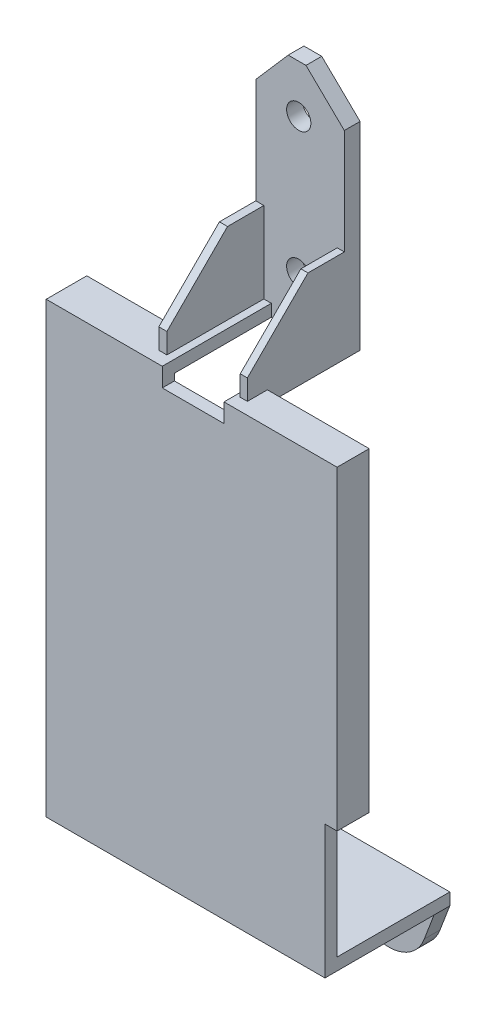
SolidWorks part; units mm, degrees
ref_plane "Plan de face" through (0, 0, 0) normal (0, 0, 1) x (1, 0, 0)
ref_plane "Plan de dessus" through (0, 0, 0) normal (0, 1, 0) x (1, 0, 0)
ref_plane "Plan de droite" through (0, 0, 0) normal (1, 0, 0) x (0, 0, -1)
sketch "Esquisse1" plane through (0, 0, 0) normal (0, 0, 1) x (1, 0, 0)
  line L0 (22, 0) -> (22, 25) construction
  line L1 (22, 25) -> (0, 25) construction
  line L2 (0, 25) -> (0, 0) construction
  line L3 (22, -10) -> (0, -10) construction
  line L5 (-1, 26) -> (-1, -11) construction
  line L6 (-1, -11) -> (16.5977, -11) construction
  line L7 (23, 0) -> (23, 26) construction
  line L8 (23, 26) -> (-1, 26) construction
  line L9 (22, 0) -> (22, 25)
  line L10 (22, 25) -> (0, 25)
  line L11 (0, 25) -> (0, -10)
  line L12 (22, -10) -> (0, -10)
  line L14 (-1, 26) -> (-1, -11)
  line L15 (-1, -11) -> (14.597, -11)
  line L16 (23, 0) -> (23, 26)
  line L17 (23, 26) -> (14.597, 26)
  line L18 (22, 0) -> (23, 0)
  line L19 (22, -10) -> (22, -11)
  line L20 (7.2927, 26) -> (7.2927, 41.3554)
  line L21 (22, -11) -> (21.1901, -13.1247)
  line L22 (15.373, -13.1247) -> (14.597, -11)
  line L23 (7.2927, 41.3554) -> (9.9639, 44.4273)
  line L24 (9.9639, 44.4273) -> (11.433, 44.4273)
  line L25 (11.433, 44.4273) -> (14.597, 41.3554)
  line L26 (14.597, 41.3554) -> (14.597, 26)
  line L27 (7.2927, 26) -> (-1, 26)
  arc A0 (15.373, -13.1247) -> (21.1901, -13.1247) centre (18.2816, -12.0623) ccw
  circle A1 centre (10.8356, 40.4859) radius 1 construction
  circle A2 centre (10.8356, 29.2822) radius 1 construction
  circle A3 centre (10.8356, 29.2822) radius 1
  circle A4 centre (10.8356, 40.4859) radius 1
  ellipse E1 centre (18.2816, -12.0623) end of major axis (19.2816, -12.0623) minor radius 1
extrude "Extrusion1" add sketch "Esquisse1" against normal blind 9.3
sketch "Esquisse2" plane through (0, 0, 0) normal (0, 0, 1) x (1, 0, 0)
  line L0 (22, 0) -> (23, 0)
  line L18 (22, 0) -> (23, 0)
  line L19 (23, 0) -> (23, 26)
  line L20 (23, 26) -> (14.597, 26)
  line L21 (14.597, 26) -> (14.597, 41.3554)
  line L22 (14.597, 41.3554) -> (11.433, 44.4273)
  line L23 (11.433, 44.4273) -> (9.9639, 44.4273)
  line L24 (9.9639, 44.4273) -> (7.2927, 41.3554)
  line L25 (7.2927, 41.3554) -> (7.2927, 26)
  line L26 (7.2927, 26) -> (-1, 26)
  line L27 (-1, 26) -> (-1, -11)
  line L28 (-1, -11) -> (14.597, -11)
  line L29 (14.597, -11) -> (15.373, -13.1247)
  line L30 (21.1901, -13.1247) -> (22, -11)
  line L31 (22, -11) -> (22, -10)
  line L32 (22, -10) -> (0, -10)
  line L33 (0, -10) -> (0, 25)
  line L34 (0, 25) -> (22, 25)
  line L35 (22, 25) -> (22, 0)
  line L37 (23, 0) -> (23, 26)
  line L44 (23, 26) -> (-1, 26)
  line L45 (-1, 26) -> (-1, -11)
  line L46 (-1, -11) -> (22, -11)
  line L49 (22, -11) -> (22, 0)
  arc A1 (15.373, -13.1247) -> (21.1901, -13.1247) centre (18.2816, -12.0623) ccw
  dimension "D1" = 0
extrude "Extrusion2" add sketch "Esquisse2" along normal blind 1
sketch "Esquisse3" plane through (23, 0, 0) normal (1, 0, 0) x (0, 0, -1)
  line L0 (9.3, 0) -> (-1, 0) construction
  line L1 (9.3, 26) -> (1.6507, 26)
  line L2 (9.3, 26) -> (9.3, 0)
  line L3 (9.3, 0) -> (1.6507, 0)
  line L4 (1.6507, 26) -> (1.6507, 0)
extrude "Enlèv. mat.-Extru.1" cut sketch "Esquisse3" against normal up to surface (8.403 mm away) up to face at (14.597, 31.7583, -5.8125)
sketch "Esquisse4" plane through (-1, 0, 0) normal (-1, 0, 0) x (0, 0, 1)
  line L0 (-9.3, -11) -> (1, -11) construction
  line L1 (-9.3, 26) -> (-2.3482, 26)
  line L2 (-9.3, 26) -> (-9.3, -11)
  line L3 (-9.3, -11) -> (-2.3482, -11)
  line L4 (-2.3482, 26) -> (-2.3482, -11)
extrude "Enlèv. mat.-Extru.2" cut sketch "Esquisse4" against normal up to surface (8.2927 mm away) up to face at (7.2927, 35.5971, -5.8125)
sketch "Esquisse5" plane through (0, 0, 1) normal (0, 0, 1) x (1, 0, 0)
  line L0 (23, 26) -> (-1, 26) construction
  line L1 (8.5767, 24.4508) -> (13.6698, 24.4508)
  line L2 (8.5767, 24.4508) -> (8.5767, 26)
  line L3 (13.6698, 26) -> (14.0104, 26)
  line L4 (13.6698, 24.4508) -> (13.6698, 26)
  line L5 (7.2927, 41.3554) -> (7.2927, 26) construction
  line L6 (7.9595, 26) -> (8.5767, 26)
  line L7 (7.9595, 26) -> (7.9595, 32.6785)
  line L8 (14.0104, 32.6785) -> (15.6702, 32.6785)
  line L9 (14.0104, 26) -> (14.0104, 32.6785)
  line L10 (7.2927, 32.6785) -> (7.9595, 32.6785)
  line L11 (7.2927, 32.6785) -> (7.2927, 45.8149)
  line L12 (7.2927, 45.8149) -> (15.6702, 45.8149)
  line L13 (15.6702, 32.6785) -> (15.6702, 45.8149)
extrude "Enlèv. mat.-Extru.3" cut sketch "Esquisse5" against normal blind 9
chamfer "Chanfrein1" distance 5 angle 45 2 edges at (7.6261, 32.6785, 0) (14.3037, 32.6785, 0)
sketch "Esquisse6" plane through (0, 0, 0) normal (0, 0, 1) x (1, 0, 0)
  line L3 (22, -11) -> (14.597, -11)
  line L4 (14.597, -11) -> (15.373, -13.1247)
  line L5 (21.1901, -13.1247) -> (22, -11)
  line L6 (22, -11) -> (14.597, -11)
  line L7 (14.597, -11) -> (15.373, -13.1247)
  line L8 (21.1901, -13.1247) -> (22, -11)
  arc A1 (15.373, -13.1247) -> (21.1901, -13.1247) centre (18.2816, -12.0623) ccw
  arc A2 (15.373, -13.1247) -> (21.1901, -13.1247) centre (18.2816, -12.0623) ccw
  dimension "D1" = 0
extrude "Enlèv. mat.-Extru.4" cut sketch "Esquisse6" against normal blind 8
